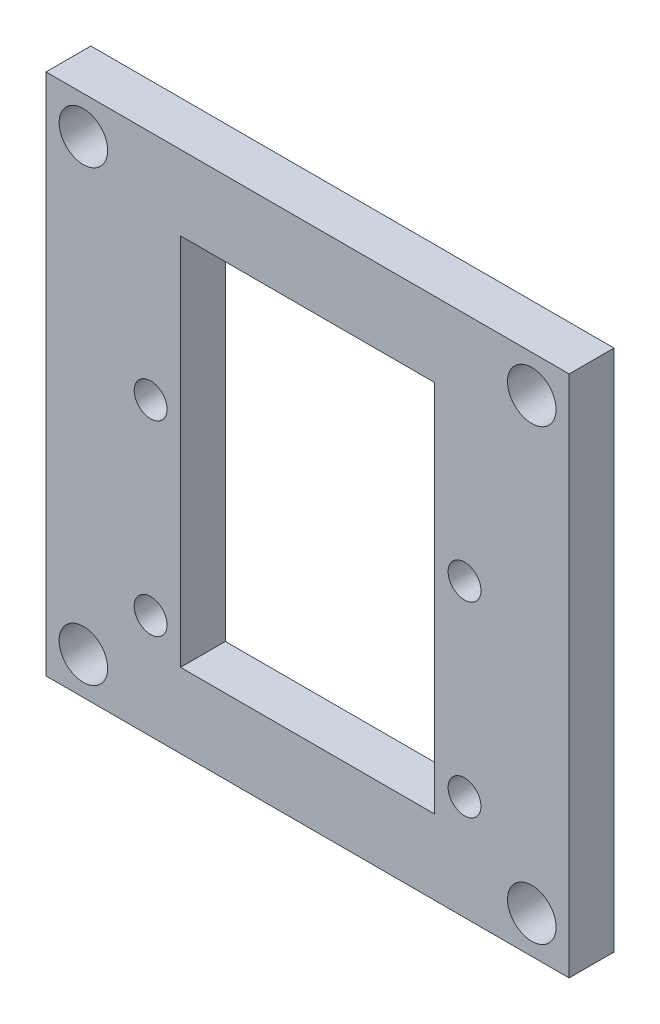
SolidWorks part; units mm, degrees
ref_plane "Front Plane" through (0, 0, 0) normal (0, 0, 1) x (1, 0, 0)
ref_plane "Top Plane" through (0, 0, 0) normal (0, 1, 0) x (1, 0, 0)
ref_plane "Right Plane" through (0, 0, 0) normal (1, 0, 0) x (0, 0, -1)
sketch "Sketch1" plane through (0, 0, 0) normal (0, 0, 1) x (1, 0, 0)
  line L0 (12.5, 25) -> (12.5, 0) construction
  line L1 (0, 0) -> (25, 0)
  line L2 (0, 0) -> (0, 25)
  line L3 (0, 25) -> (25, 25)
  line L4 (25, 0) -> (25, 25)
  line L5 (-5, -5) -> (30, -5)
  line L6 (-5, -5) -> (-5, 30)
  line L7 (-5, 30) -> (30, 30)
  line L8 (30, -5) -> (30, 30)
  line L9 (-5, -5) -> (30, 30) construction
  line L10 (-5, 30) -> (30, -5) construction
  line L11 (4, 25) -> (4, 0)
  line L12 (21, 25) -> (21, 0)
  line L13 (-5, 12.5) -> (30, 12.5) construction
  circle A0 centre (2, 14.5) radius 1.1
  circle A1 centre (2, 2) radius 1.1
  circle A2 centre (23, 2) radius 1.1
  circle A3 centre (23, 14.5) radius 1.1
  circle A4 centre (-2.5, 27.5) radius 1.6243
  circle A5 centre (27.5, 27.5) radius 1.6243
  circle A6 centre (27.5, -2.5) radius 1.6243
  circle A7 centre (-2.5, -2.5) radius 1.6243
  point P5 (12.5, 12.5)
  dimension "D6" = 2.2
  dimension "D7" = 14.5
  dimension "D9" = 2.2
  dimension "D1" = 25
  dimension "D2" = 5
  dimension "D3" = 5
  dimension "D4" = 5
  dimension "D5" = 5
  dimension "D8" = 2
  dimension "D10" = 2
  dimension "D11" = 4
  dimension "D12" = 2.5
extrude "Boss-Extrude1" add sketch "Sketch1" along normal blind 3 contours L3 L12 L1 L4 A2 A3 | L11 L3 L2 L1 A1 A0 | L5 L8 L7 L6 L4 L1 L2 L3
